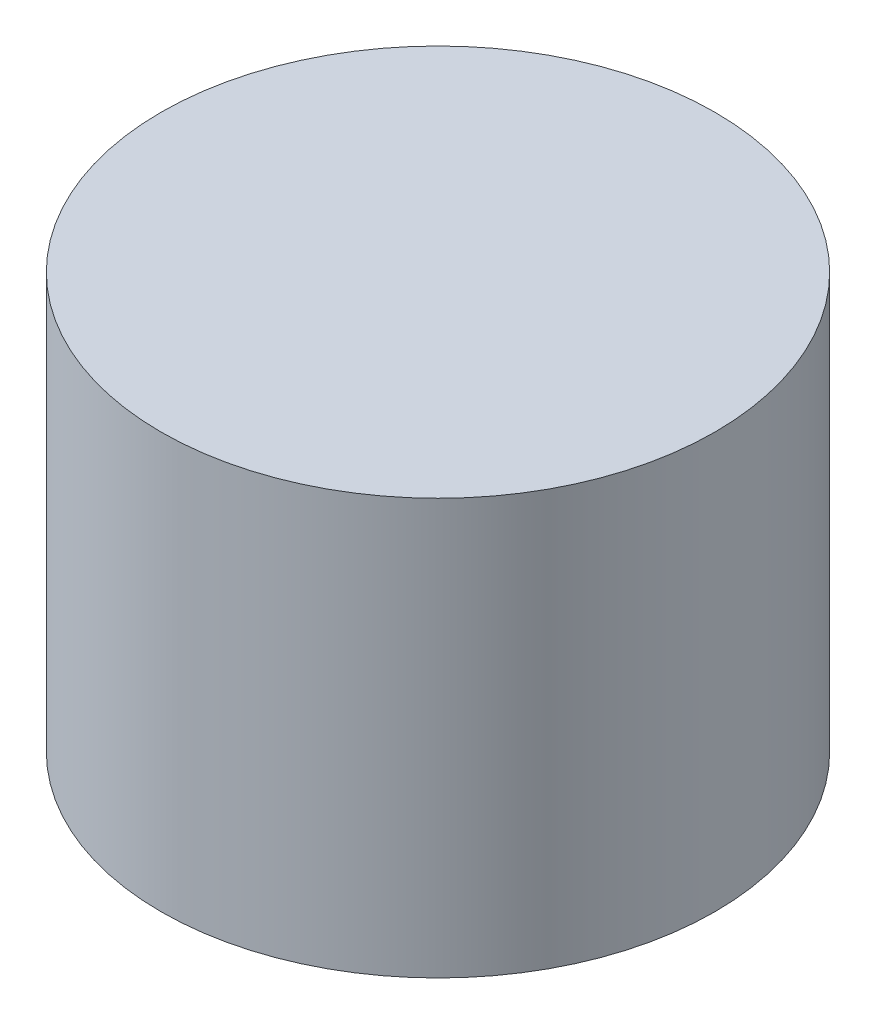
SolidWorks part; units mm, degrees
material "1060 合金"
ref_plane "前视基准面" through (0, 0, 0) normal (0, 0, 1) x (1, 0, 0)
ref_plane "上视基准面" through (0, 0, 0) normal (0, 1, 0) x (1, 0, 0)
ref_plane "右视基准面" through (0, 0, 0) normal (1, 0, 0) x (0, 0, -1)
sketch "草图1" plane through (0, 0, 0) normal (0, 1, 0) x (1, 0, 0)
  circle A0 centre (0, 0) radius 40
  dimension "D1" = 80
extrude "凸台-拉伸1" add sketch "草图1" along normal blind 60
